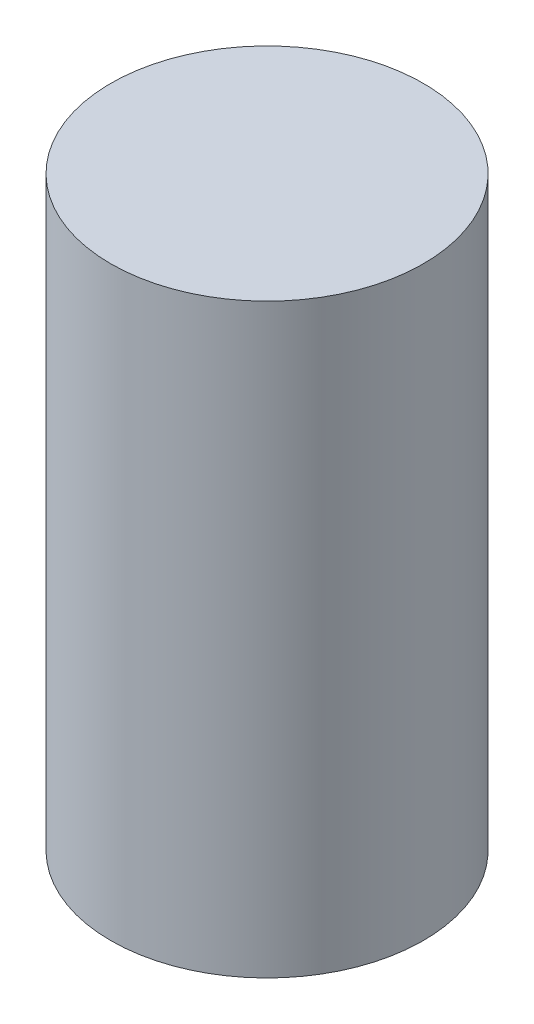
SolidWorks part; units mm, degrees
ref_plane "Front Plane" through (0, 0, 0) normal (0, 0, 1) x (1, 0, 0)
ref_plane "Top Plane" through (0, 0, 0) normal (0, 1, 0) x (1, 0, 0)
ref_plane "Right Plane" through (0, 0, 0) normal (1, 0, 0) x (0, 0, -1)
sketch "Sketch1" plane through (0, 0, 0) normal (0, 1, 0) x (1, 0, 0)
  circle A0 centre (0, 0) radius 40
  dimension "D1" = 80
extrude "Boss-Extrude1" add sketch "Sketch1" along normal blind 150
